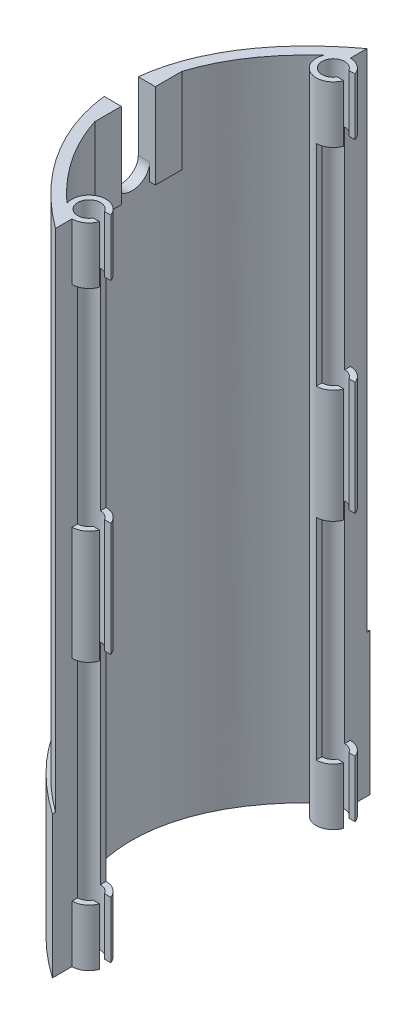
SolidWorks part; units mm, degrees
ref_plane "前视基准面" through (0, 0, 0) normal (0, 0, 1) x (1, 0, 0)
ref_plane "上视基准面" through (0, 0, 0) normal (0, 1, 0) x (1, 0, 0)
ref_plane "右视基准面" through (0, 0, 0) normal (1, 0, 0) x (0, 0, -1)
sketch "草图1" plane through (0, 0, 0) normal (0, 1, 0) x (1, 0, 0)
  line L0 (-50, 27.4154) -> (-50, 24.5)
  line L2 (0, 0) -> (-77.6844, 0) construction
  line L4 (-48.2679, 22.5) -> (-47.1716, 22.5)
  line L6 (-48.2679, 20.5) -> (-47.1716, 20.5)
  line L7 (-50, 21.5) -> (-53.6696, 21.5) construction
  line L8 (-50, -21.5) -> (-53.6696, -21.5) construction
  line L9 (-48.2679, -20.5) -> (-47.1716, -20.5)
  line L10 (-48.2679, -22.5) -> (-47.1716, -22.5)
  line L12 (-50, -27.4154) -> (-50, -24.5)
  arc A1 (-52.7826, 22.6212) -> (-47.1716, 20.5) centre (-50, 21.5) ccw
  arc A2 (-48.2679, 22.5) -> (-48.2679, 20.5) centre (-50, 21.5) ccw
  arc A3 (-47.1716, 22.5) -> (-50, 24.5) centre (-50, 21.5) ccw
  arc A4 (-47.1716, -22.5) -> (-50, -24.5) centre (-50, -21.5) cw
  arc A5 (-48.2679, -22.5) -> (-48.2679, -20.5) centre (-50, -21.5) cw
  arc A6 (-52.7826, -22.6212) -> (-47.1716, -20.5) centre (-50, -21.5) cw
  ellipse E0 centre (0, 0) end of major axis (66, 0) minor radius 42 (-50, 27.4154) -> (-50, -27.4154) ccw
  ellipse E1 centre (0, 0) end of major axis (-64, 0) minor radius 40 (-52.7826, 22.6212) -> (-52.7826, -22.6212) ccw
  point P18 (-49.4024, 20.7292)
  point P26 (-48.1545, 20.7679)
  dimension "D6" = 4
  dimension "D7" = 6
  dimension "D1" = 132
  dimension "D2" = 84
  dimension "D3" = 2
  dimension "D4" = 2
  dimension "D5" = 2
  dimension "D8" = 21.5
  dimension "D9" = 50
extrude "凸台-拉伸1" add sketch "草图1" along normal blind 114
sketch "草图2" plane through (0, 0, 0) normal (0, -1, 0) x (1, 0, 0)
  line L0 (-50, -24.9687) -> (-50, -27.9571)
  line L1 (-50, -24.5) -> (-50, -27.4154) construction
  line L2 (-50, 24.9687) -> (-50, 27.9571)
  line L3 (-50, 27.4154) -> (-50, 24.5) construction
  line L4 (0, 0) -> (0, 59.5575) construction
  ellipse E0 centre (0, 0) end of major axis (-67, 0) minor radius 42 (-50, 27.9571) -> (-50, -27.9571) ccw
  ellipse E2 centre (0, 0) end of major axis (-64, 0) minor radius 40 (-50, 24.9687) -> (-50, -24.9687) ccw
  ellipse E3 centre (0, 0) end of major axis (-64, 0) minor radius 40 (-52.7826, 22.6212) -> (-52.7826, -22.6212) ccw construction
  point P2 (0, 43.4664)
  point P10 (0, 38.52)
  dimension "D1" = 84
  dimension "D2" = 67
  dimension "D3" = 2
extrude "凸台-拉伸2" add sketch "草图2" against normal blind 25
sketch "草图3" plane through (0, 0, 0) normal (1, 0, 0) x (0, 0, -1)
  line L0 (0, 0) -> (0, 130.7021) construction
  line L1 (3, 114) -> (-3, 114)
  line L2 (27.4154, 114) -> (-27.4154, 114) construction
  line L3 (-3, 114) -> (-3, 102)
  line L5 (3, 114) -> (3, 102)
  arc A0 (-3, 102) -> (3, 102) centre (0, 102) ccw
  point P3 (0, 104)
  point P11 (0, 114)
  point P12 (0, 0)
  point P13 (0, 0)
  point P14 (0, 104)
  dimension "D3" = 3
  dimension "D1" = 6
  dimension "D2" = 12
extrude "切除-拉伸1" cut sketch "草图3" against normal through all
sketch "草图4" plane through (0, 114, 0) normal (0, 1, 0) x (1, 0, 0)
  line L1 (-63.8197, 3) -> (-62.8197, 3)
  line L2 (-63.8197, 3) -> (-63.8197, 8)
  line L3 (-63.8197, 8) -> (-62.8197, 8)
  line L4 (-62.8197, 3) -> (-62.8197, 8)
  line L5 (-63.8197, -3) -> (-62.8197, -3)
  line L6 (-63.8197, -3) -> (-63.8197, -8)
  line L7 (-63.8197, -8) -> (-62.8197, -8)
  line L8 (-62.8197, -3) -> (-62.8197, -8)
  dimension "D1" = 1
  dimension "D2" = 5
  dimension "D3" = 5
extrude "凸台-拉伸3" add sketch "草图4" against normal blind 15
sketch "草图5" plane through (0, 0, 0) normal (0, 0, 1) x (1, 0, 0)
  line L0 (-50, 114) -> (-50, 25) construction
  line L1 (-50, 104) -> (-40.2352, 104)
  line L2 (-50, 104) -> (-50, 67)
  line L3 (-50, 67) -> (-40.2352, 67)
  line L4 (-40.2352, 104) -> (-40.2352, 67)
  line L5 (-50, 57) -> (-17.8699, 57) construction
  line L6 (-50, 114) -> (-50, 0) construction
  line L7 (-40.2352, 10) -> (-40.2352, 47)
  line L8 (-50, 47) -> (-40.2352, 47)
  line L9 (-50, 10) -> (-50, 47)
  line L10 (-50, 10) -> (-40.2352, 10)
  line L11 (-50, 114) -> (-65.8314, 114) construction
  dimension "D1" = 20
  dimension "D2" = 10
extrude "切除-拉伸2" cut sketch "草图5" against normal through all and the other way through all
